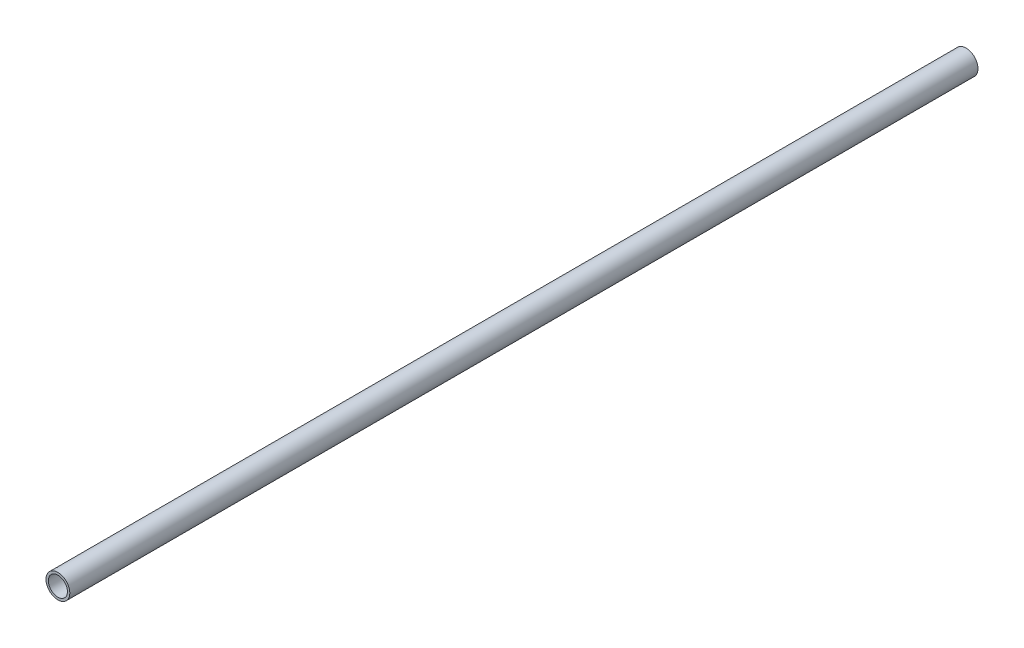
SolidWorks part; units mm, degrees
ref_plane "Front Plane" through (0, 0, 0) normal (0, 0, 1) x (1, 0, 0)
ref_plane "Top Plane" through (0, 0, 0) normal (0, 1, 0) x (1, 0, 0)
ref_plane "Right Plane" through (0, 0, 0) normal (1, 0, 0) x (0, 0, -1)
sketch "Sketch1" plane through (0, 0, 0) normal (0, 0, 1) x (1, 0, 0)
  circle A0 centre (0, 0) radius 4
  circle A1 centre (0, 0) radius 5
  dimension "D2" = 10
  dimension "D1" = 1
extrude "Boss-Extrude1" add sketch "Sketch1" along normal mid plane 381
